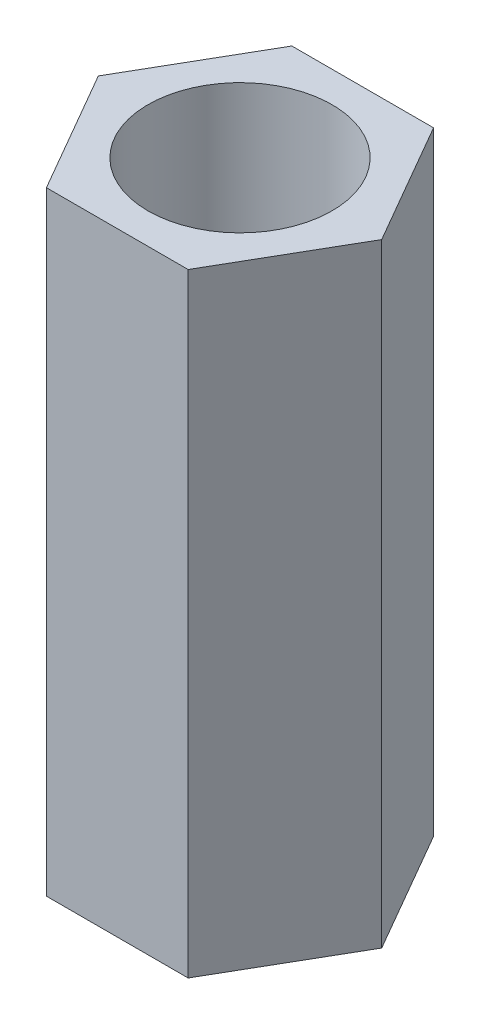
SolidWorks part; units mm, degrees
ref_plane "Front Plane" through (0, 0, 0) normal (0, 0, 1) x (1, 0, 0)
ref_plane "Top Plane" through (0, 0, 0) normal (0, 1, 0) x (1, 0, 0)
ref_plane "Right Plane" through (0, 0, 0) normal (1, 0, 0) x (0, 0, -1)
sketch "草图1" plane through (0, 0, 0) normal (0, 1, 0) x (1, 0, 0)
  line L1 (2.3094, 0) -> (1.1547, 2)
  line L2 (1.1547, 2) -> (-1.1547, 2)
  line L3 (-1.1547, 2) -> (-2.3094, 0)
  line L4 (-2.3094, 0) -> (-1.1547, -2)
  line L5 (-1.1547, -2) -> (1.1547, -2)
  line L6 (1.1547, -2) -> (2.3094, 0)
  circle A0 centre (0, 0) radius 2 construction
  dimension "D1" = 4
extrude "凸台-拉伸1" add sketch "草图1" along normal blind 10
sketch "草图2" plane through (0, 10, 0) normal (0, 1, 0) x (1, 0, 0)
  circle A0 centre (0, 0) radius 1.5
  dimension "D1" = 3
extrude "切除-拉伸1" cut sketch "草图2" against normal through all
